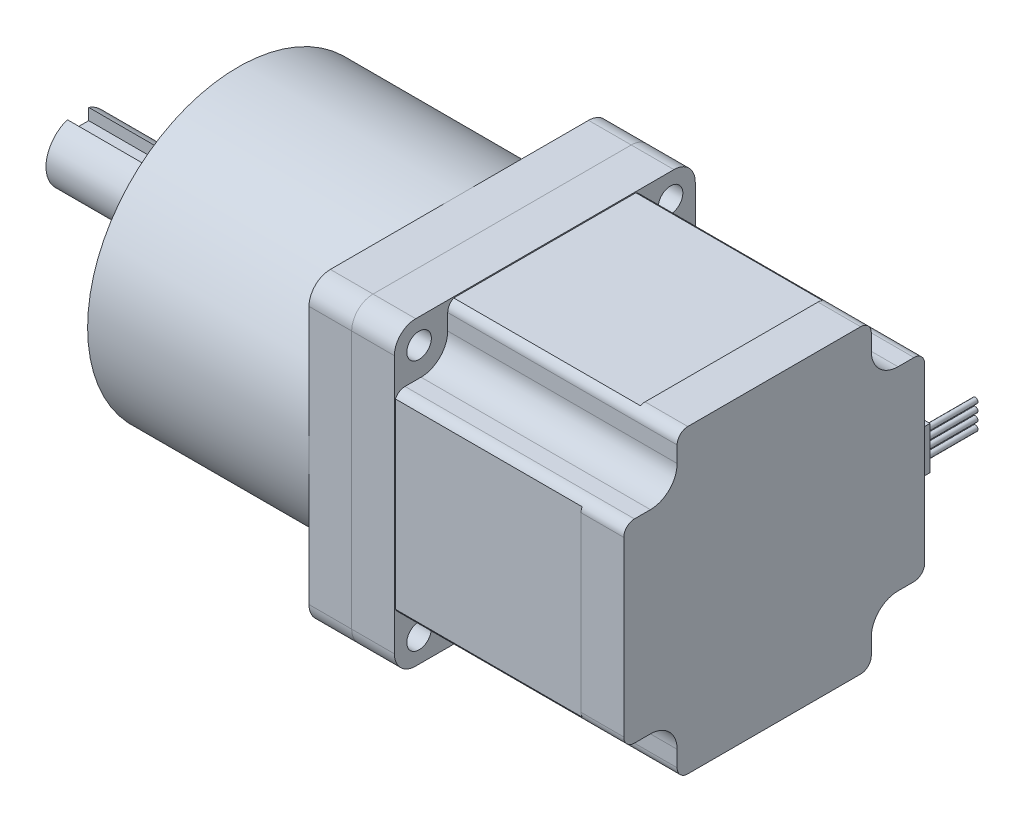
SolidWorks part; units mm, degrees
ref_plane "前视基准面" through (0, 0, 0) normal (0, 0, 1) x (1, 0, 0)
ref_plane "上视基准面" through (0, 0, 0) normal (0, 1, 0) x (1, 0, 0)
ref_plane "右视基准面" through (0, 0, 0) normal (1, 0, 0) x (0, 0, -1)
sketch "草图1" plane through (0, 0, 0) normal (1, 0, 0) x (0, 0, -1)
  line L1 (28.2, -28.2) -> (-28.2, -28.2)
  line L2 (28.2, -28.2) -> (28.2, 28.2)
  line L3 (28.2, 28.2) -> (-28.2, 28.2)
  line L4 (-28.2, -28.2) -> (-28.2, 28.2)
  line L5 (28.2, -28.2) -> (-28.2, 28.2) construction
  line L6 (28.2, 28.2) -> (-28.2, -28.2) construction
  point P0 (0, 0)
  dimension "D1" = 56.4
  dimension "D2" = 56.4
extrude "凸台-拉伸1" add sketch "草图1" along normal mid plane 51
sketch "草图7" plane through (0, 0, 0) normal (1, 0, 0) x (0, 0, -1)
  line L1 (28, 28) -> (-28, 28)
  line L2 (28, 28) -> (28, -28)
  line L3 (28, -28) -> (-28, -28)
  line L4 (-28, 28) -> (-28, -28)
  line L5 (28, 28) -> (-28, -28) construction
  line L6 (28, -28) -> (-28, 28) construction
  line L7 (28.2, -28.2) -> (-28.2, -28.2)
  line L8 (28.2, -28.2) -> (28.2, 28.2)
  line L9 (28.2, 28.2) -> (-28.2, 28.2)
  line L10 (-28.2, -28.2) -> (-28.2, 28.2)
  line L11 (28.2, -28.2) -> (-28.2, 28.2) construction
  line L12 (28.2, 28.2) -> (-28.2, -28.2) construction
  point P0 (0, 0)
  point P6 (0, 0)
  dimension "D1" = 56
  dimension "D2" = 56
  dimension "D3" = 56.4
  dimension "D4" = 56.4
extrude "切除-拉伸1" cut sketch "草图7" against normal mid plane 35
sketch "草图2" plane through (-25.5, 0, 0) normal (-1, 0, 0) x (0, 0, 1)
  circle A0 centre (0, 0) radius 19.05
  dimension "D1" = 38.1
extrude "凸台-拉伸2" add sketch "草图2" along normal blind 1.6
sketch "草图3" plane through (-27.1, 0, 0) normal (-1, 0, 0) x (0, 0, 1)
  circle A0 centre (0, 0) radius 3.175
  dimension "D1" = 6.35
extrude "凸台-拉伸3" add sketch "草图3" along normal blind 19
sketch "草图10" plane through (0, 0, -28.2) normal (0, 0, -1) x (-1, 0, 0)
  line L0 (-25.5, -28.2) -> (-25.5, 28.2) construction
  line L1 (-23.5, -4) -> (-20.5, -4)
  line L2 (-23.5, -4) -> (-23.5, 4)
  line L3 (-23.5, 4) -> (-20.5, 4)
  line L4 (-20.5, -4) -> (-20.5, 4)
  line L5 (-23.5, -4) -> (-20.5, 4) construction
  line L6 (-23.5, 4) -> (-20.5, -4) construction
  point P0 (-22, 0)
  dimension "D1" = 8
  dimension "D2" = 3
  dimension "D3" = 2
  dimension "D4" = 0
extrude "凸台-拉伸4" add sketch "草图10" along normal blind 3
sketch "草图11" plane through (0, 0, -31.2) normal (0, 0, -1) x (-1, 0, 0)
  line L2 (-23.5, -4) -> (-20.5, -4) construction
  line L3 (-23.5, 4) -> (-23.5, -4) construction
  circle A2 centre (-22, -2.5) radius 0.5
  circle A3 centre (-22, -1) radius 0.5
  circle A4 centre (-22, 0.5) radius 0.5
  circle A5 centre (-22, 2) radius 0.5
  point P0 (-22, -4)
  dimension "D2" = 1.5
  dimension "D3" = 1.5
  dimension "D4" = 1
  dimension "D5" = 1
  dimension "D6" = 1
  dimension "D7" = 1
  dimension "D8" = 1.5
  dimension "D9" = 1.5
  dimension "D10" = 1.5
  dimension "D13" = 1.5
  dimension "D14" = 1.5
  dimension "D15" = 1.5
extrude "凸台-拉伸5" add sketch "草图11" along normal blind 10
sketch "草图12" plane through (25.5, 0, 0) normal (1, 0, 0) x (0, 0, -1)
  line L1 (28.2, -28.2) -> (18.2, -28.2)
  line L2 (28.2, -28.2) -> (28.2, -18.2)
  line L3 (28.2, -18.2) -> (18.2, -18.2)
  line L4 (18.2, -28.2) -> (18.2, -18.2)
  line L5 (-28.2, -28.2) -> (-18.2, -28.2)
  line L6 (-28.2, -28.2) -> (-28.2, -18.2)
  line L7 (-28.2, -18.2) -> (-18.2, -18.2)
  line L8 (-18.2, -28.2) -> (-18.2, -18.2)
  line L9 (-28.2, 28.2) -> (-18.2, 28.2)
  line L10 (-28.2, 28.2) -> (-28.2, 18.2)
  line L11 (-28.2, 18.2) -> (-18.2, 18.2)
  line L12 (-18.2, 28.2) -> (-18.2, 18.2)
  line L13 (28.2, 28.2) -> (18.2, 28.2)
  line L14 (28.2, 28.2) -> (28.2, 18.2)
  line L15 (28.2, 18.2) -> (18.2, 18.2)
  line L16 (18.2, 28.2) -> (18.2, 18.2)
  dimension "D1" = 10
  dimension "D2" = 10
  dimension "D3" = 10
  dimension "D4" = 10
  dimension "D5" = 10
  dimension "D6" = 10
  dimension "D7" = 10
  dimension "D8" = 10
extrude "切除-拉伸2" cut sketch "草图12" against normal blind 43
fillet "圆角2" radius 5 4 edges at (4, -18.2, 18.2) (4, 18.2, 18.2) (4, 18.2, -18.2) (4, -18.2, -18.2)
fillet "圆角3" radius 2 8 edges at (21.5, 28.2, -18.2) (21.5, 28.2, 18.2) (21.5, 18.2, 28.2) (21.5, -18.2, 28.2) (21.5, -28.2, 18.2) (21.5, -28.2, -18.2) (21.5, -18.2, -28.2) (21.5, 18.2, -28.2)
hole_wizard "Ø4.6 (4.6) 直径孔1" positions "草图5" profile "草图4" hole size "Ø4.6" standard "Gb"
sketch "草图5" plane through (-25.5, 0, 0) normal (-1, 0, 0) x (0, 0, 1)
  line L0 (38.17, 0) -> (-38.17, 0) construction
  line L1 (0, -31.02) -> (0, 31.02) construction
  point P0 (-23.57, 23.57)
  point P2 (23.57, 23.57)
  point P4 (23.57, -23.57)
  point P6 (-23.57, -23.57)
  dimension "D1" = 47.14
  dimension "D2" = 47.14
  dimension "D3" = 23.57
  dimension "D4" = 23.57
  dimension "D5" = 47.14
  dimension "D6" = 47.14
  dimension "D7" = 23.57
sketch "草图4" plane through (-25.5, 23.57, -23.57) normal (0, 1, 0) x (0, 0, 1)
  line L0 (0, 0) -> (0, 11.382)
  line L1 (0, 11.382) -> (2.3, 10)
  line L2 (2.3, 10) -> (2.3, 0)
  line L5 (2.3, 0) -> (0, 0)
  line L10 (0, 11.382) -> (-2.3, 10) construction
  line L11 (0, -6.35) -> (0, 107.95) construction
  dimension "孔直径" = 4.6
  dimension "孔深度" = 10
  dimension "导头角度" = 118
fillet "圆角1" radius 4 4 edges at (-21.5, -28.2, -28.2) (-21.5, -28.2, 28.2) (-21.5, 28.2, -28.2) (-21.5, 28.2, 28.2)
sketch "草图13" plane through (-25.5, 0, 0) normal (-1, 0, 0) x (0, 0, 1)
  line L4 (-24.2, -28.2) -> (24.2, -28.2)
  line L5 (28.2, -24.2) -> (28.2, 24.2)
  line L6 (24.2, 28.2) -> (-24.2, 28.2)
  line L7 (-28.2, 24.2) -> (-28.2, -24.2)
  line L8 (-24.2, -28.2) -> (24.2, -28.2)
  line L9 (28.2, -24.2) -> (28.2, 24.2)
  line L10 (24.2, 28.2) -> (-24.2, 28.2)
  line L11 (-28.2, 24.2) -> (-28.2, -24.2)
  circle A0 centre (-23.57, 23.57) radius 2.3 construction
  circle A1 centre (23.57, 23.57) radius 2.3 construction
  circle A2 centre (-23.57, -23.57) radius 2.3 construction
  circle A3 centre (23.57, -23.57) radius 2.3 construction
  arc A4 (24.2, -28.2) -> (28.2, -24.2) centre (24.2, -24.2) ccw
  arc A5 (28.2, 24.2) -> (24.2, 28.2) centre (24.2, 24.2) ccw
  arc A6 (-24.2, 28.2) -> (-28.2, 24.2) centre (-24.2, 24.2) ccw
  arc A7 (-28.2, -24.2) -> (-24.2, -28.2) centre (-24.2, -24.2) ccw
  arc A8 (24.2, -28.2) -> (28.2, -24.2) centre (24.2, -24.2) ccw
  arc A9 (28.2, 24.2) -> (24.2, 28.2) centre (24.2, 24.2) ccw
  arc A10 (-24.2, 28.2) -> (-28.2, 24.2) centre (-24.2, 24.2) ccw
  arc A11 (-28.2, -24.2) -> (-24.2, -28.2) centre (-24.2, -24.2) ccw
  circle A12 centre (-23.57, 23.57) radius 2.3
  circle A13 centre (23.57, 23.57) radius 2.3
  circle A14 centre (-23.57, -23.57) radius 2.3
  circle A15 centre (23.57, -23.57) radius 2.3
  dimension "D1" = 0
extrude "凸台-拉伸6" add sketch "草图13" along normal blind 8 separate body
sketch "草图14" plane through (-33.5, 0, 0) normal (-1, 0, 0) x (0, 0, 1)
  circle A0 centre (0, 0) radius 28.2
extrude "凸台-拉伸7" add sketch "草图14" along normal blind 41.5
sketch "草图15" plane through (-75, 0, 0) normal (-1, 0, 0) x (0, 0, 1)
  circle A0 centre (0, 0) radius 16
  dimension "D1" = 32
extrude "凸台-拉伸8" add sketch "草图15" along normal blind 2
sketch "草图16" plane through (-77, 0, 0) normal (-1, 0, 0) x (0, 0, 1)
  circle A0 centre (0, 0) radius 6
  dimension "D1" = 12
extrude "凸台-拉伸9" add sketch "草图16" along normal blind 28
sketch "草图17" plane through (0, 0, 0) normal (0, 1, 0) x (1, 0, 0)
  line L0 (-105, 0) -> (-87, 0) construction
  line L1 (-105, 6) -> (-105, -6) construction
  line L2 (-105, 2) -> (-87, 2)
  line L3 (-105, -2) -> (-87, -2)
  arc A0 (-105, 2) -> (-105, -2) centre (-105, 0) ccw
  arc A1 (-87, -2) -> (-87, 2) centre (-87, 0) ccw
  point P5 (-96, 0)
  dimension "D2" = 20
  dimension "D1" = 4
extrude "切除-拉伸4" cut sketch "草图17" along normal blind 28 from offset 3.5
sketch "草图18" plane through (-75, 0, 0) normal (-1, 0, 0) x (0, 0, 1)
  line L1 (15.9099, -15.9099) -> (-15.9099, -15.9099)
  line L2 (15.9099, -15.9099) -> (15.9099, 15.9099)
  line L3 (15.9099, 15.9099) -> (-15.9099, 15.9099)
  line L4 (-15.9099, -15.9099) -> (-15.9099, 15.9099)
  line L5 (15.9099, -15.9099) -> (-15.9099, 15.9099) construction
  line L6 (15.9099, 15.9099) -> (-15.9099, -15.9099) construction
  point P0 (0, 0)
  dimension "D1" = 45
hole_wizard "M5 螺纹孔1" positions "3D草图1" profile "草图19" tap size "M5" standard "Gb"
sketch3d "3D草图1"
  point P0 (-75, 15.9099, -15.9099)
  point P3 (-75, 15.9099, 15.9099)
  point P6 (-75, -15.9099, -15.9099)
  point P9 (-75, -15.9099, 15.9099)
sketch "草图19" plane through (-75, 15.9099, -15.9099) normal (0, 1, 0) x (0, 0, 1)
  line L0 (0, 0) -> (0, 13.6618)
  line L1 (0, 13.6618) -> (2.1, 12.4)
  line L2 (2.1, 12.4) -> (2.1, 0)
  line L5 (2.1, 0) -> (0, 0)
  line L10 (0, 13.6618) -> (-2.1, 12.4) construction
  line L11 (0, -6.35) -> (0, 107.95) construction
  dimension "螺纹孔钻头直径" = 4.2
  dimension "螺纹孔钻头深度" = 12.4
  dimension "导头角度" = 118
